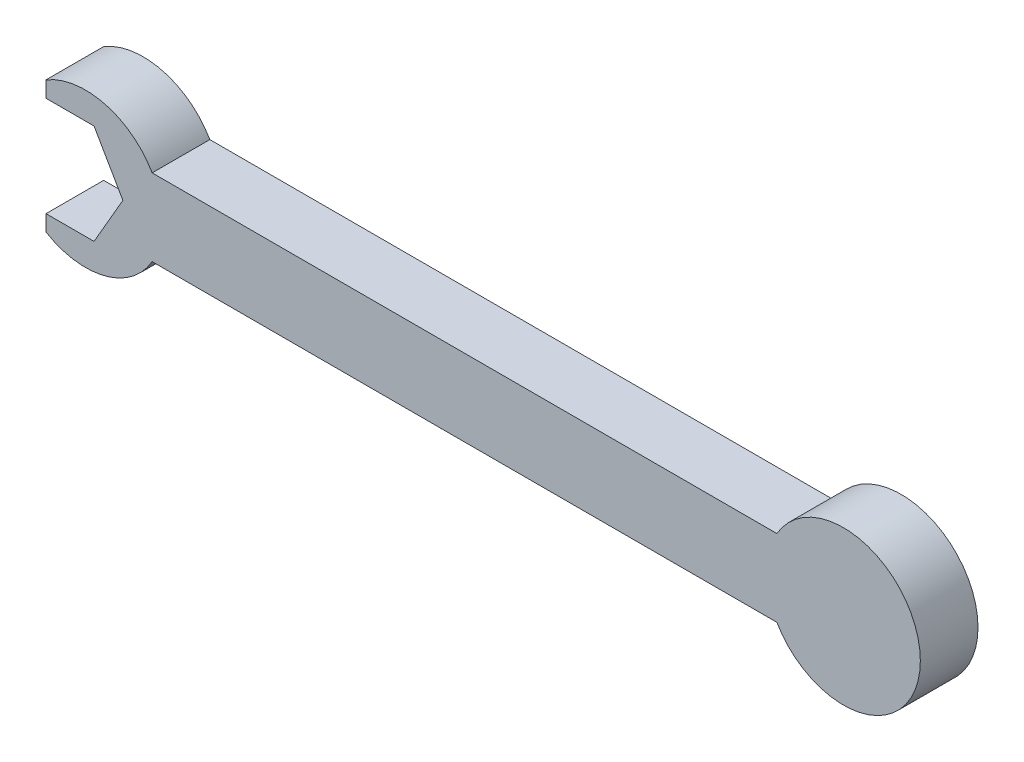
SolidWorks part; units mm, degrees
ref_plane "Front Plane" through (0, 0, 0) normal (0, 0, 1) x (1, 0, 0)
ref_plane "Top Plane" through (0, 0, 0) normal (0, 1, 0) x (1, 0, 0)
ref_plane "Right Plane" through (0, 0, 0) normal (1, 0, 0) x (0, 0, -1)
other "Configuration Table"
sketch "Sketch1" plane through (0, 0, 0) normal (0, 0, 1) x (1, 0, 0)
  line L1 (8.7988, 5.08) -> (91.3488, 5.08)
  line L2 (8.7988, 5.08) -> (8.7988, -5.08)
  line L3 (8.7988, -5.08) -> (91.3488, -5.08)
  line L4 (91.3488, 5.08) -> (91.3488, -5.08)
  circle A0 centre (0, 0) radius 10.16
  circle A1 centre (100.1476, 0) radius 10.16
  point P9 (8.7988, 0)
  point P10 (0, 0)
  dimension "D1" = 20.32
  dimension "D2" = 20.32
  dimension "D3" = 82.55
  dimension "D4" = 10.16
extrude "Boss-Extrude1" add sketch "Sketch1" along normal mid plane 7.62 contours L2 A0 | A1 L1 A0 L3 | L4 A1 | L4 A1 | L2 A0
sketch "Sketch2" plane through (0, 0, 0) normal (0, 0, 1) x (1, 0, 0)
  line L0 (-5.2311, 8.7099) -> (-5.2311, -8.7099)
  line L1 (103.8138, -6.35) -> (107.48, 0)
  line L2 (107.48, 0) -> (103.8138, 6.35)
  line L3 (103.8138, 6.35) -> (96.4815, 6.35)
  line L4 (96.4815, 6.35) -> (92.8153, 0)
  line L5 (92.8153, 0) -> (96.4815, -6.35)
  line L6 (96.4815, -6.35) -> (103.8138, -6.35)
  line L14 (4.9289, 0) -> (1.1189, 6.5991)
  line L15 (1.1189, 6.5991) -> (-6.5011, 6.5991)
  line L16 (-6.5011, 6.5991) -> (-10.3111, 0)
  line L17 (8.7988, -5.08) -> (91.3488, -5.08)
  line L18 (91.3488, 5.08) -> (8.7988, 5.08)
  line L19 (8.7988, -5.08) -> (91.3488, -5.08)
  line L20 (91.3488, 5.08) -> (8.7988, 5.08)
  line L21 (-10.3111, 0) -> (-6.5011, -6.5991)
  line L22 (-6.5011, -6.5991) -> (1.1189, -6.5991)
  line L23 (1.1189, -6.5991) -> (4.9289, 0)
  circle A0 centre (100.1476, 0) radius 6.35 construction
  circle A1 centre (-2.6911, 0) radius 6.5991 construction
  arc A2 (8.7988, 5.08) -> (8.7988, -5.08) centre (0, 0) ccw construction
  arc A5 (8.7988, 5.08) -> (8.7988, -5.08) centre (0, 0) ccw
  arc A6 (91.3488, -5.08) -> (91.3488, 5.08) centre (100.1476, 0) ccw
  arc A7 (8.7988, 5.08) -> (8.7988, -5.08) centre (0, 0) ccw
  arc A8 (91.3488, -5.08) -> (91.3488, 5.08) centre (100.1476, 0) ccw
  point P1 (0, 0)
  point P12 (6.7584, 0)
  point P22 (2.4519, 6.5991)
  point P25 (2.4519, 6.5991)
  point P26 (-5.2311, 8.7099)
  dimension "D2" = 10.16
  dimension "D1" = 12.7
  dimension "D3" = 0
  dimension "D4" = 6.35
  dimension "D5" = 13.1982
extrude "Cut-Extrude1" cut sketch "Sketch2" against normal through all both and the other way through all contours L22 L23 L14 L15 L0 | L16 A7 L21 L22 L0 L15 | L0 A7 L16 L15 | L21 A7 L0 L22
equation "\"GAUGE\"= SWITCH ( \"Thickness\" < 0.9 , 0 , \"Thickness\" < 1.1 , 20 , \"Thickness\" < 1.6 , 16 , \"Thickness\" < 2.1 , 14 , \"Thickness\" < 3.1 , 11 , \"Thickness\" < 4.8 , 7 , \"Thickness\" > 4.8 , 0 )"
